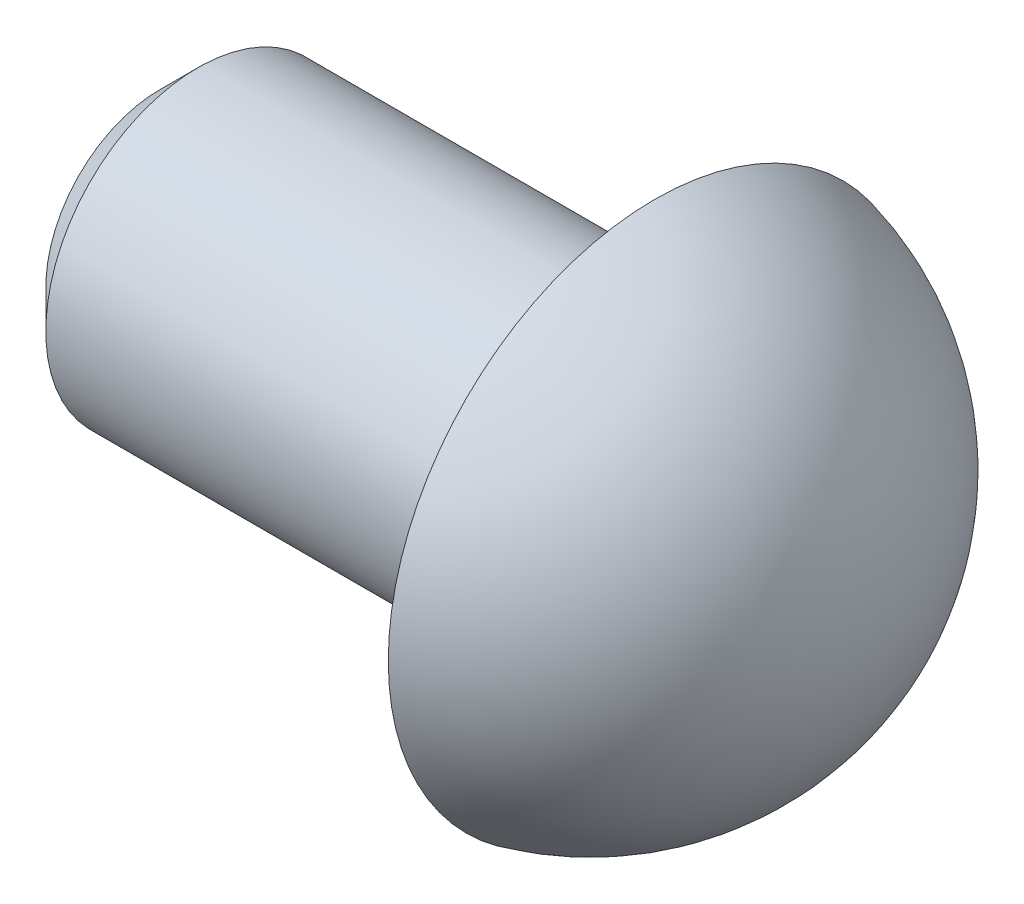
SolidWorks part; units mm, degrees
ref_plane "Front Plane" through (0, 0, 0) normal (0, 0, 1) x (1, 0, 0)
ref_plane "Top Plane" through (0, 0, 0) normal (0, 1, 0) x (1, 0, 0)
ref_plane "Right Plane" through (0, 0, 0) normal (1, 0, 0) x (0, 0, -1)
sketch "Sketch1" plane through (0, 0, 0) normal (1, 0, 0) x (0, 0, -1)
  circle A0 centre (0, 0) radius 2
  dimension "D1" = 4
extrude "Boss-Extrude1" add sketch "Sketch1" against normal blind 6.5
sketch "Sketch2" plane through (0, 0, 0) normal (0, 1, 0) x (1, 0, 0)
  line L0 (-3.4721, 0) -> (2.7574, 0) construction
  line L1 (2.7574, 0) -> (0, 0)
  line L2 (0, 0) -> (0, 3.5)
  arc A0 (0, 3.5) -> (2.7574, 0) centre (-0.8426, 0) cw
  dimension "D2" = 3.6
  dimension "D1" = 3.5
revolve "Revolve1" add sketch "Sketch2" angle 360 about L0
chamfer "Chamfer1" distance 0.5 angle 45 1 edges at (-6.5, 0, -2)
